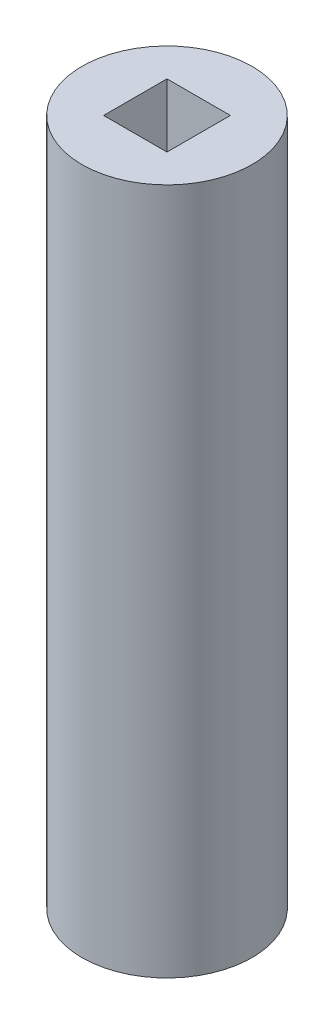
SolidWorks part; units mm, degrees
ref_plane "Front Plane" through (0, 0, 0) normal (0, 0, 1) x (1, 0, 0)
ref_plane "Top Plane" through (0, 0, 0) normal (0, 1, 0) x (1, 0, 0)
ref_plane "Right Plane" through (0, 0, 0) normal (1, 0, 0) x (0, 0, -1)
sketch "Sketch1" plane through (0, 0, 0) normal (0, 1, 0) x (1, 0, 0)
  line L1 (-19.05, -19.05) -> (19.05, -19.05)
  line L2 (-19.05, -19.05) -> (-19.05, 19.05)
  line L3 (-19.05, 19.05) -> (19.05, 19.05)
  line L4 (19.05, -19.05) -> (19.05, 19.05)
  line L5 (-19.05, -19.05) -> (19.05, 19.05) construction
  line L6 (-19.05, 19.05) -> (19.05, -19.05) construction
  circle A0 centre (0, 0) radius 51.1302
  dimension "D3" = 102.2604
  dimension "D1" = 38.1
  dimension "D2" = 38.1
extrude "Boss-Extrude1" add sketch "Sketch1" along normal blind 406.4
sketch "Sketch2" plane through (0, 0, 0) normal (0, -1, 0) x (1, 0, 0)
  circle A0 centre (0, 0) radius 51.1302 construction
  circle A1 centre (0, 0) radius 51.1302
extrude "Boss-Extrude2" add sketch "Sketch2" along normal blind 6.35
